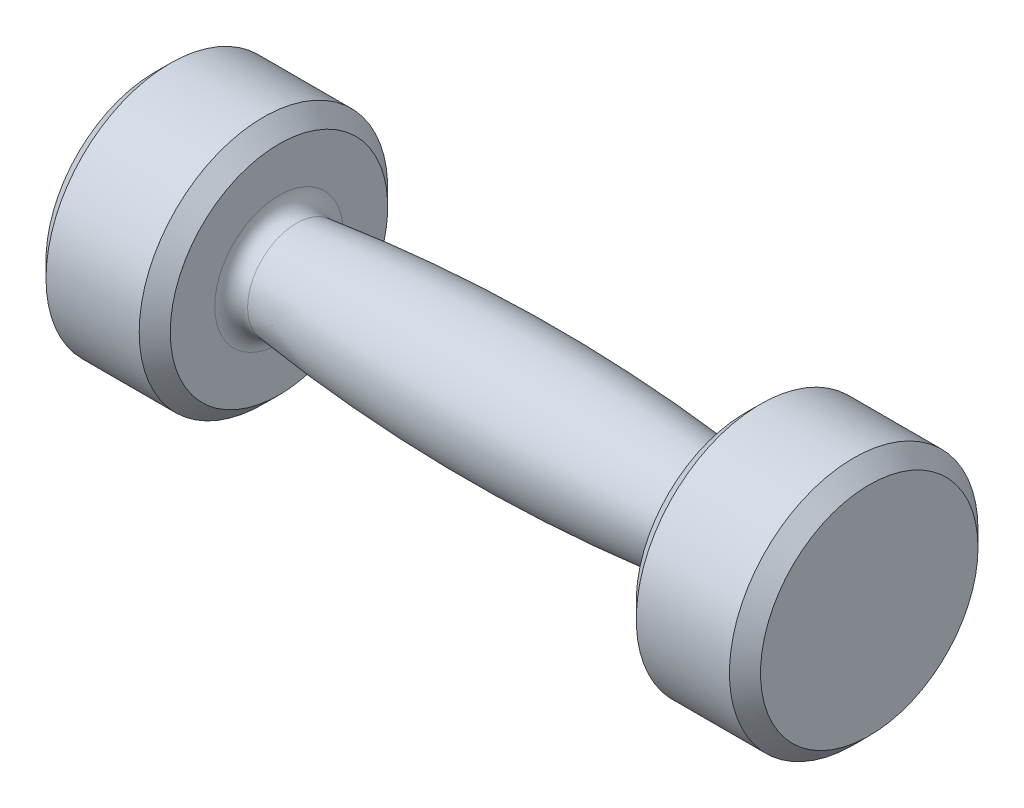
SolidWorks part; units mm, degrees
ref_plane "Front Plane" through (0, 0, 0) normal (0, 0, 1) x (1, 0, 0)
ref_plane "Top Plane" through (0, 0, 0) normal (0, 1, 0) x (1, 0, 0)
ref_plane "Right Plane" through (0, 0, 0) normal (1, 0, 0) x (0, 0, -1)
sketch "Sketch5" plane through (0, 0, 0) normal (1, 0, 0) x (0, 0, -1)
  circle A0 centre (0, 0) radius 15
  dimension "D1" = 30
extrude "Boss-Extrude1" add sketch "Sketch5" along normal mid plane 230
sketch "Sketch6" plane through (115, 0, 0) normal (1, 0, 0) x (0, 0, -1)
  circle A0 centre (0, 0) radius 40
  dimension "D1" = 80
extrude "Boss-Extrude2" add sketch "Sketch6" against normal blind 40
sketch "Sketch7" plane through (-115, 0, 0) normal (-1, 0, 0) x (0, 0, 1)
  circle A0 centre (0, 0) radius 40
  dimension "D1" = 80
extrude "Boss-Extrude3" add sketch "Sketch7" against normal blind 40
sketch "Sketch9" plane through (0, 0, 0) normal (0, 0, 1) x (1, 0, 0)
  line L0 (0, 0) -> (-192.8492, 0) construction
  line L1 (-75, 15) -> (75, 15)
  arc A0 (-75, 15) -> (75, 15) centre (0, -545) cw
  point P3 (0, 20)
  dimension "D1" = 20
revolve "Revolve1" add sketch "Sketch9" angle 360 about L0
fillet "Fillet2" radius 5 2 edges at (75, 0, -15) (-75, 0, -15)
chamfer "Chamfer1" distance 5 angle 45 4 edges at (75, 0, -40) (115, 0, -40) (-75, 0, 40) (-115, 0, 40)
